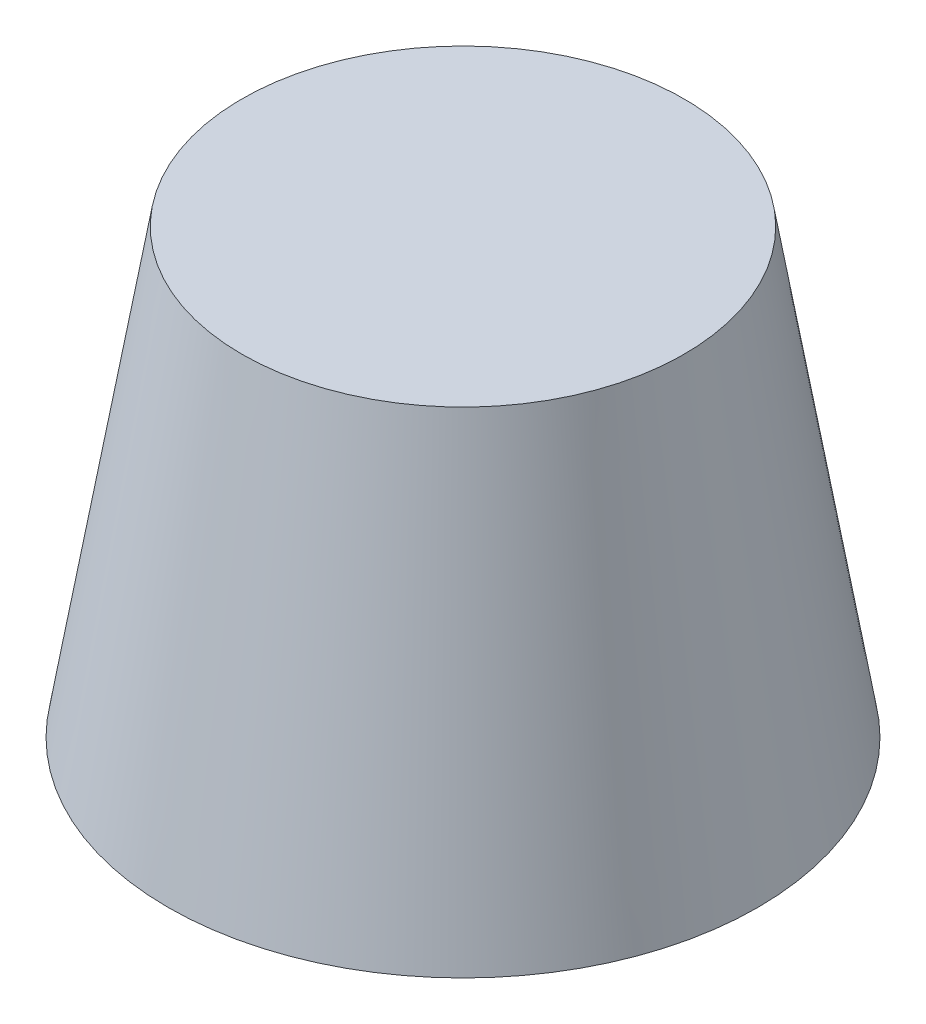
SolidWorks part; units mm, degrees
ref_plane "Front Plane" through (0, 0, 0) normal (0, 0, 1) x (1, 0, 0)
ref_plane "Top Plane" through (0, 0, 0) normal (0, 1, 0) x (1, 0, 0)
ref_plane "Right Plane" through (0, 0, 0) normal (1, 0, 0) x (0, 0, -1)
sketch "Sketch1" plane through (0, 0, 0) normal (0, 1, 0) x (1, 0, 0)
  circle A0 centre (0, 0) radius 6
ref_plane "Plane1" through (0, -12, 0) normal (0, 1, 0) x (1, 0, 0)
sketch "Sketch2" plane through (0, -12, 0) normal (0, 1, 0) x (1, 0, 0)
  circle A0 centre (0, 0) radius 8
loft "Loft1" add profiles "Sketch1", "Sketch2"
sketch "Sketch4" plane through (0, -12, 0) normal (0, -1, 0) x (1, 0, 0)
  line L0 (-2.7423, -1.55) -> (2.7423, -1.55)
  line L1 (6.6001, 0) -> (-6.6001, 0) construction
  circle A0 centre (0, 0) radius 3.15
  dimension "D1" = 1.55
extrude "Cut-Extrude1" cut sketch "Sketch4" against normal blind 10 contours L0 A0
